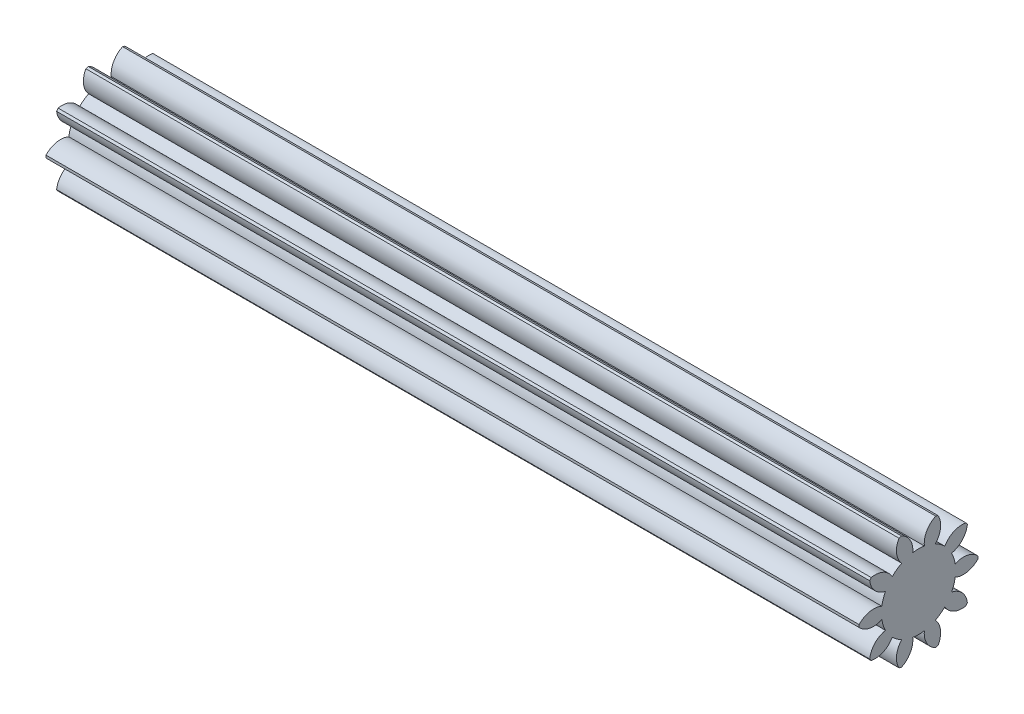
SolidWorks part; units mm, degrees
ref_plane "Plane1" through (0, 0, 0) normal (0, 0, 1) x (1, 0, 0)
ref_plane "Plane2" through (0, 0, 0) normal (0, 1, 0) x (1, 0, 0)
ref_plane "Plane3" through (0, 0, 0) normal (1, 0, 0) x (0, 0, -1)
sketch "HoldingSke" plane through (0, 0, 0) normal (0, 1, 0) x (1, 0, 0)
  line L0 (0, 0) -> (0.4924, -0.0868)
  line L1 (-15, 0) -> (100, 0) construction
  line L2 (0, 0) -> (-2.1039, 2.3779)
  line L3 (0, 0) -> (-11.863, 4.5341)
  line L4 (0, 0) -> (8.5048, 1.4996)
  line L5 (0, 0) -> (-46.8476, -17.4728)
  line L6 (0, 0) -> (-9.9476, -6.7116)
  line L7 (-2.1039, 2.3779) -> (8.6586, 51.2059)
  line L8 (-76.2, 54.61) -> (-76.1, 54.61)
  line L9 (-71.009, 38.7566) -> (-53.1078, 45.2721)
  line L10 (-76.2, 71.12) -> (104.1128, 71.12)
  line L11 (0, 0) -> (-12, 0)
  line L12 (-76.2, 101.6) -> (-76.133, 101.6)
  line L13 (24.9733, 27.94) -> (52.9518, 28.4284)
  line L14 (24.9733, 27.94) -> (24.9743, 27.94)
  line L15 (24.9733, 27.94) -> (100.4006, 29.5858)
  line L16 (-63.627, -2) -> (-12.827, -2)
  circle A0 centre (0, 0) radius 0.4
  circle A1 centre (0, 0) radius 7.499
  circle A2 centre (0, 0) radius 37.5
  circle A3 centre (0, 0) radius 0.4
  dimension "MHD" = 14.998
  dimension "Hub_dia" = 75
  dimension "Bore" = 0.8
  dimension "MBD" = 0.8
  dimension "Num_teeth" = 10
  dimension "Pitch" = 0.5
  dimension "Overall_len" = 50
  dimension "Show_teeth" = 10
  dimension "Thickness" = 12
  dimension "OAL" = 50.0001
  dimension "T_dim" = 0.1
  dimension "Ap" = 20
  dimension "H" = 19.05
  dimension "Pitch_radius" = 180.3128
  dimension "Width" = 12
  dimension "Backlash" = 0.067
  dimension "Addendum_fac" = 1
  dimension "Dedendum_fac" = 1.25
  dimension "Clearance_fac" = 0.25
  dimension "Dedendum_add" = 0.001
  dimension "Module" = 2
sketch "BasProSke" plane through (0, 0, 0) normal (0, 1, 0) x (1, 0, 0)
  line L0 (-10, 0) -> (60, 0) construction
  line L1 (0, 0) -> (0, 12)
  line L2 (0, 0) -> (164.0924, 0)
  line L3 (164.0924, 0) -> (164.0924, 12)
  line L4 (164.0924, 12) -> (0, 12)
  dimension "Thickness" = 164.0924
  dimension "Diameter" = 24
revolve "Base-Revolve" add sketch "BasProSke" angle 360 about L0
sketch "TooCutSke" plane through (0, 0, 0) normal (1, 0, 0) x (0, 0, -1)
  line L1 (0, 0) -> (0, 107) construction
  line L2 (0, 0) -> (-1.6814, 9.8576) construction
  line L3 (0, 0) -> (-6.1153, 18.8209) construction
  line L4 (-1.6814, 9.8576) -> (-3.0576, 9.4105) construction
  arc A0 (1.1737, 7.4066) -> (-1.1737, 7.4066) centre (0, 0) ccw
  arc A1 (3.4979, 11.5054) -> (-3.4979, 11.5054) centre (0, 0) ccw
  circle A2 centre (0, 0) radius 10 construction
  circle A3 centre (0, 0) radius 9.3969 construction
  arc A4 (-1.1737, 7.4066) -> (-3.4979, 11.5054) centre (-5.1477, 7.8615) ccw
  arc A5 (3.4979, 11.5054) -> (1.1737, 7.4066) centre (5.1477, 7.8615) ccw
  dimension "Root_dia" = 14.998
  dimension "Overcut_dia" = 24.0508
  dimension "Pitch_dia" = 20
  dimension "Base_dia" = 18.7939
  dimension "Flank_rad" = 4
  dimension "Half_ang" = 18
  dimension "Half_CT" = 1.4471
extrude "ToothCut" cut sketch "TooCutSke" along normal through all
fillet "Breaks" [suppressed] radius 0.04
fillet "RootFillets" [suppressed] radius 0.501
pattern_circular "TeethCuts" count 10 every 36 about axis through (-10, 0, 0) along (1, 0, 0) of "ToothCut", "RootFillets", "Breaks"
sketch "HubNeaOneSke" plane through (0, 0, 0) normal (-1, 0, 0) x (0, 0, 1)
  circle A0 centre (0, 0) radius 7.499
  dimension "Diameter" = 14.998
extrude "HubNearOne" [suppressed] add sketch "HubNeaOneSke" along normal blind 38.0001
sketch "HubNeaBotSke" plane through (0, 0, 0) normal (-1, 0, 0) x (0, 0, 1)
  circle A0 centre (0, 0) radius 7.499
  dimension "Diameter" = 14.998
extrude "HubNearBoth" [suppressed] add sketch "HubNeaBotSke" along normal blind 19
ref_plane "FarPln" through (164.0924, 0, 0) normal (1, 0, 0) x (0, 0, -1)
sketch "HubFarSke" plane through (164.0924, 0, 0) normal (1, 0, 0) x (0, 0, -1)
  circle A0 centre (0, 0) radius 7.499
  dimension "Diameter" = 14.998
extrude "HubFar" [suppressed] add sketch "HubFarSke" along normal blind 19
sketch "BorSke" plane through (0, 0, 0) normal (1, 0, 0) x (0, 0, -1)
  circle A0 centre (0, 0) radius 0.4
  dimension "Diameter" = 0.8
extrude "Bore" cut sketch "BorSke" along normal mid plane 100.0001
sketch "KeySke" plane through (0, 0, 0) normal (1, 0, 0) x (0, 0, -1)
  line L0 (-0.05, 0) -> (-0.05, 0.5)
  line L1 (-0.05, 0.5) -> (0.05, 0.5)
  line L2 (0.05, 0.5) -> (0.05, 0)
  line L3 (0, 0) -> (0, 34) construction
  line L4 (-0.05, 0) -> (0.05, 0)
  dimension "Offset" = 0.5
  dimension "Width" = 0.1
extrude "Keyway" [suppressed] cut sketch "KeySke" along normal mid plane 100.0001
pattern_circular "Keyway2" [suppressed] count 2 every 90 about axis through (-10, 0, 0) along (1, 0, 0)
scale "Scale1" scale about centroid uniform scaling yes scale factor 0.399752
equation "' \"Module@HoldingSke\" = 6.35"
equation "' \"Num_teeth@HoldingSke\" = 12"
equation "' \"Ap@HoldingSke\" =  20"
equation "' \"Ap@HoldingSke\" = 20"
equation "' \"Width@HoldingSke\" = 0.5 * 25.4"
equation "' \"Hub_dia@HoldingSke\"= 1 * 25.4"
equation "' \"Hub_dia@HoldingSke\" = 1 * 25.4"
equation "' \"Overall_len@HoldingSke\" = 1.0 * 25.4"
equation "' \"Bore@HoldingSke\" = 0.75 * 25.4"
equation "' \"T_dim@HoldingSke\" = 0.1 * 25.4"
equation "' \"Width@KeySke\" = 0.25 * 25.4"
equation "' \"Show_teeth@HoldingSke\" = 13"
equation "' \"Backlash@HoldingSke\" = 0.009 * 25.4"
equation "' \"Addendum_fac@HoldingSke\" = 1.0"
equation "' \"Dedendum_fac@HoldingSke\" = 1.25"
equation "' \"Dedendum_add@HoldingSke\" = 0.00005 * 25.4"
equation "' \"Clearance_fac@HoldingSke\" = 0.25"
equation "\"Pitch@HoldingSke\" = 1 / \"Module@HoldingSke\""
equation "\"Overcut_dia@TooCutSke\" = (\"Num_teeth@HoldingSke\" + 2 * \"Addendum_fac@HoldingSke\") / \"Pitch@HoldingSke\" + 0.002 * 25.4"
equation "\"Pitch_dia@TooCutSke\" = \"Num_teeth@HoldingSke\" / \"Pitch@HoldingSke\""
equation "\"Base_dia@TooCutSke\" = \"Num_teeth@HoldingSke\" / \"Pitch@HoldingSke\" * cos((\"Ap@HoldingSke\"  * 3.14159265 / 180))"
equation "\"Root_dia@TooCutSke\" = (\"Num_teeth@HoldingSke\" + 2) / \"Pitch@HoldingSke\" - 2 * (\"Addendum_fac@HoldingSke\" + \"Dedendum_fac@HoldingSke\") / \"Pitch@HoldingSke\" - \"Dedendum_add@HoldingSke\" * 2"
equation "\"Half_ang@TooCutSke\" = 180 / \"Num_teeth@HoldingSke\""
equation "\"Half_CT@TooCutSke\" = \"Num_teeth@HoldingSke\" / \"Pitch@HoldingSke\" * sin((3.14159265 / 2 / \"Num_teeth@HoldingSke\")) / 2 - 7 * \"Backlash@HoldingSke\" / 4"
equation "\"Flank_rad@TooCutSke\" = \"Num_teeth@HoldingSke\" / \"Pitch@HoldingSke\" / 5"
equation "\"Radius@RootFillets\" = \"Clearance_fac@HoldingSke\" / \"Pitch@HoldingSke\" + \"Dedendum_add@HoldingSke\""
equation "\"Break_rad@Breaks\" = 0.02 / \"Pitch@HoldingSke\""
equation "\"Thickness@HoldingSke\" = \"Width@HoldingSke\""
equation "\"OAL@HoldingSke\" = \"Thickness@HoldingSke\""
equation "\"MHD@HoldingSke\" = (\"Num_teeth@HoldingSke\" + 2) / \"Pitch@HoldingSke\" - 2 * (\"Addendum_fac@HoldingSke\" + \"Dedendum_fac@HoldingSke\")  / \"Pitch@HoldingSke\" - \"Dedendum_add@HoldingSke\" * 2"
equation "\"MBD@HoldingSke\" = (\"Num_teeth@HoldingSke\" + 2) / \"Pitch@HoldingSke\" - 2 * (\"Addendum_fac@HoldingSke\" + \"Dedendum_fac@HoldingSke\")  / \"Pitch@HoldingSke\" - \"Dedendum_add@HoldingSke\" * 2 - 0.002 * 25.4"
equation "\"MHD@HoldingSke\" = ((sgn( \"MHD@HoldingSke\" - \"Hub_dia@HoldingSke\" )-1)*( \"MHD@HoldingSke\" - \"Hub_dia@HoldingSke\" ))/-2+ \"Hub_dia@HoldingSke\""
equation "\"MBD@HoldingSke\" = ((sgn( \"MBD@HoldingSke\" - \"Bore@HoldingSke\" )-1)*( \"MBD@HoldingSke\" - \"Bore@HoldingSke\" ))/-2+ \"Bore@HoldingSke\""
equation "\"OAL@HoldingSke\" = ((sgn( \"OAL@HoldingSke\" - \"Overall_len@HoldingSke\" )+1)*( \"OAL@HoldingSke\" - \"Overall_len@HoldingSke\" ))/2 + \"Overall_len@HoldingSke\" + 0.000002 * 25.4"
equation "\"Num_teeth@TeethCuts\" = int( \"Show_teeth@HoldingSke\" ) + 1"
equation "\"Num_teeth@TeethCuts\" = ((sgn( \"Num_teeth@TeethCuts\" - \"Num_teeth@HoldingSke\" )-1)*( \"Num_teeth@TeethCuts\" - \"Num_teeth@HoldingSke\" ))/-2+ \"Num_teeth@HoldingSke\""
equation "\"Num_teeth@TeethCuts\" = ((sgn( \"Num_teeth@TeethCuts\" - 2.0)+1)*( \"Num_teeth@TeethCuts\" - 2.0))/2 +2.0"
equation "\"Angle@TeethCuts\" = 360.0 / \"Num_teeth@HoldingSke\""
equation "\"Diameter@BasProSke\" = (\"Num_teeth@HoldingSke\" + 2 * \"Addendum_fac@HoldingSke\") / \"Pitch@HoldingSke\""
equation "\"Thickness@BasProSke\"=(35.6153564+30)*85.028/34"
equation "' \"Fillet_rad@BasProSke\" =  \"Thickness@HoldingSke\" * 0.05"
equation "' \"Fillet_rad@BasProSke\" = \"Thickness@HoldingSke\" * 0.05"
equation "\"MHD@HoldingSke\" = ((sgn( \"MHD@HoldingSke\" - \"Root_dia@TooCutSke\" )-1)*( \"MHD@HoldingSke\" - \"Root_dia@TooCutSke\" ))/-2+ \"Root_dia@TooCutSke\""
equation "\"Diameter@HubNeaOneSke\" = \"MHD@HoldingSke\""
equation "\"Length@HubNearOne\" = \"OAL@HoldingSke\" - \"Thickness@BasProSke\""
equation "\"Diameter@HubNeaBotSke\" = \"MHD@HoldingSke\""
equation "\"Length@HubNearBoth\" = ( \"OAL@HoldingSke\" - \"Thickness@BasProSke\" ) / 2.0"
equation "\"Thickness@FarPln\" = \"Thickness@BasProSke\""
equation "\"Diameter@HubFarSke\" = \"MHD@HoldingSke\""
equation "\"Length@HubFar\" = ( \"OAL@HoldingSke\" - \"Thickness@BasProSke\" ) / 2.0"
equation "\"Diameter@BorSke\" = \"MBD@HoldingSke\""
equation "\"D1@Bore\" = \"OAL@HoldingSke\" * 2.0"
equation "\"D1@Keyway\" = \"OAL@HoldingSke\" * 2.0"
equation "\"Offset@KeySke\" = \"T_dim@HoldingSke\" + \"MBD@HoldingSke\" / 2.0"
